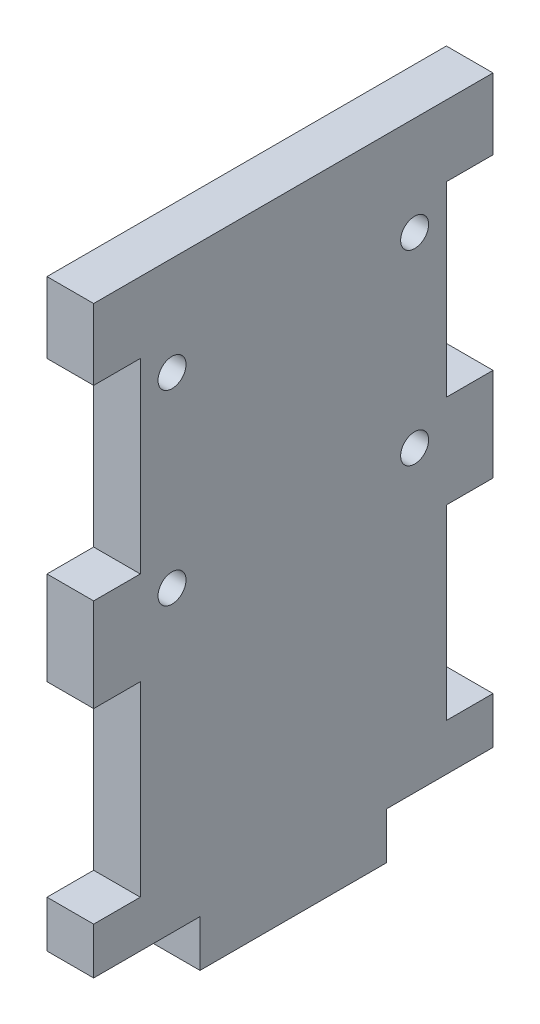
SolidWorks part; units mm, degrees
ref_plane "Front Plane" through (0, 0, 0) normal (0, 0, 1) x (1, 0, 0)
ref_plane "Top Plane" through (0, 0, 0) normal (0, 1, 0) x (1, 0, 0)
ref_plane "Right Plane" through (0, 0, 0) normal (1, 0, 0) x (0, 0, -1)
sketch "Sketch1" plane through (0, 0, 0) normal (1, 0, 0) x (0, 0, -1)
  line L0 (14.478, 0) -> (14.478, 6.35)
  line L1 (14.478, 0) -> (39.878, 0)
  line L2 (39.878, 0) -> (39.878, 6.35)
  line L3 (39.878, 6.35) -> (54.356, 6.35)
  line L4 (54.356, 6.35) -> (54.356, 12.7)
  line L5 (27.178, 6.35) -> (27.178, 85.852) construction
  line L6 (7.112, 6.35) -> (7.112, 85.852) construction
  line L7 (47.244, 6.35) -> (47.244, 85.852) construction
  line L8 (10.668, 6.35) -> (10.668, 85.852) construction
  line L9 (54.356, 85.852) -> (0, 85.852)
  line L10 (0, 85.852) -> (0, 76.2)
  line L11 (0, 6.35) -> (14.478, 6.35)
  line L12 (0, 6.35) -> (0, 0) construction
  line L13 (0, 0) -> (14.478, 0) construction
  line L14 (43.688, 6.35) -> (43.688, 85.852) construction
  line L15 (14.478, 6.35) -> (39.878, 6.35) construction
  line L17 (10.668, 72.39) -> (43.688, 72.39) construction
  line L18 (10.668, 46.99) -> (43.688, 46.99) construction
  line L34 (54.356, 76.2) -> (48.006, 76.2)
  line L35 (48.006, 76.2) -> (48.006, 50.8)
  line L36 (48.006, 50.8) -> (54.356, 50.8)
  line L37 (54.356, 76.2) -> (54.356, 85.852)
  line L38 (54.356, 38.1) -> (48.006, 38.1)
  line L39 (48.006, 38.1) -> (48.006, 12.7)
  line L40 (48.006, 12.7) -> (54.356, 12.7)
  line L41 (54.356, 38.1) -> (54.356, 50.8)
  line L42 (6.35, 12.7) -> (0, 12.7)
  line L43 (6.35, 38.1) -> (6.35, 12.7)
  line L44 (0, 38.1) -> (6.35, 38.1)
  line L45 (0, 76.2) -> (6.35, 76.2)
  line L46 (6.35, 76.2) -> (6.35, 50.8)
  line L47 (6.35, 50.8) -> (0, 50.8)
  line L48 (0, 50.8) -> (0, 38.1)
  line L49 (0, 12.7) -> (0, 6.35)
  circle A0 centre (10.668, 72.39) radius 1.905
  circle A1 centre (43.688, 72.39) radius 1.905
  circle A2 centre (43.688, 46.99) radius 1.905
  circle A3 centre (10.668, 46.99) radius 1.905
  point P8 (27.178, 85.852)
  dimension "D10" = 3.81
  dimension "D11" = 3.81
  dimension "D12" = 3.81
  dimension "D13" = 3.81
  dimension "D1" = 25.4
  dimension "D2" = 6.35
  dimension "D3" = 7.112
  dimension "D4" = 6.35
  dimension "D5" = 79.502
  dimension "D6" = 40.132
  dimension "D7" = 33.02
  dimension "D8" = 25.4
  dimension "D9" = 46.99
  dimension "D14" = 69.85
  dimension "D15" = 25.4
  dimension "D16" = 25.4
  dimension "D17" = 31.75
extrude "Extrude1" add sketch "Sketch1" along normal blind 6.35
